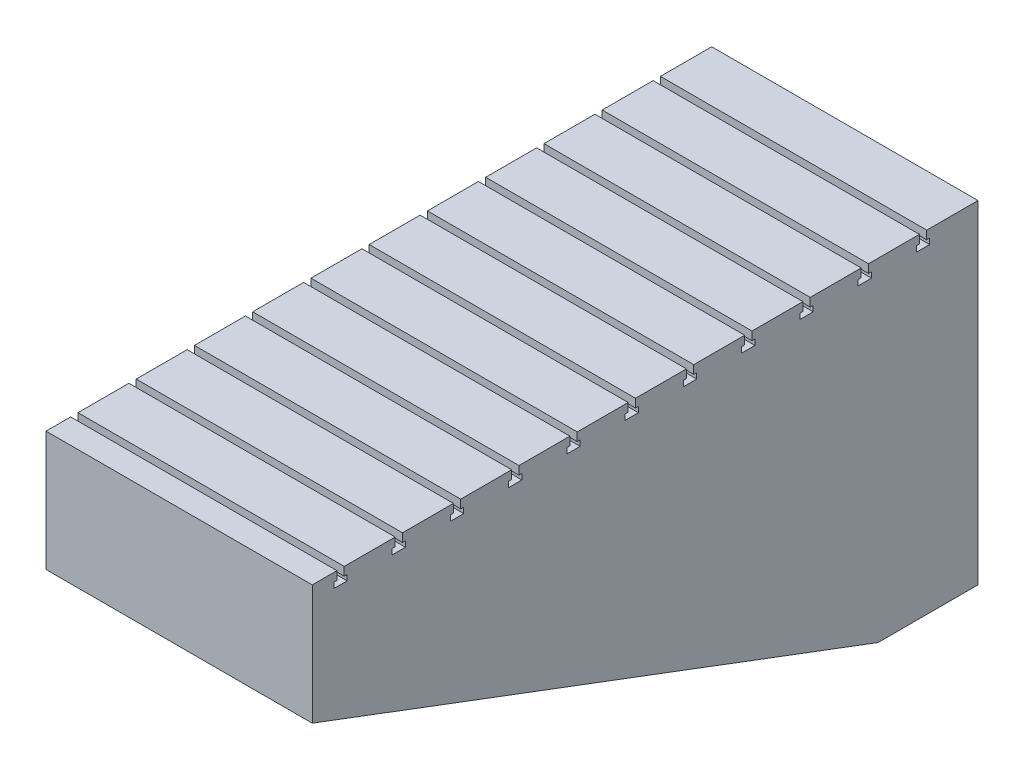
SolidWorks part; units mm, degrees
ref_plane "Front Plane" through (0, 0, 0) normal (0, 0, 1) x (1, 0, 0)
ref_plane "Top Plane" through (0, 0, 0) normal (0, 1, 0) x (1, 0, 0)
ref_plane "Right Plane" through (0, 0, 0) normal (1, 0, 0) x (0, 0, -1)
sketch "Sketch4" plane through (0, 0, 0) normal (1, 0, 0) x (0, 0, -1)
  line L0 (0, 0) -> (-2000, 0)
  line L1 (-2000, 0) -> (-2000, -360)
  line L2 (-2000, -360) -> (-300, -1000)
  line L3 (-300, -1000) -> (0, -1000)
  line L4 (0, -1000) -> (0, 0)
  dimension "D1" = 2000
  dimension "D2" = 1000
  dimension "D3" = 360
  dimension "D4" = 300
extrude "Boss-Extrude1" add sketch "Sketch4" along normal blind 800
sketch "Sketch6" plane through (0, 0, 0) normal (1, 0, 0) x (0, 0, -1)
  line L0 (0, 0) -> (-2000, 0) construction
  line L1 (-154, 0) -> (-176, 0)
  line L2 (-154, 0) -> (-154, -25.3)
  line L3 (-154, -25.3) -> (-145.15, -25.3)
  line L4 (-145.15, -25.3) -> (-145.15, -42)
  line L5 (-145.15, -42) -> (-184.85, -42)
  line L6 (-184.85, -42) -> (-184.85, -25.3)
  line L7 (-184.85, -25.3) -> (-176, -25.3)
  line L8 (-176, -25.3) -> (-176, 0)
  line L9 (-165, 58.1636) -> (-165, 256.6562) construction
  line L11 (0, -1000) -> (0, 0) construction
  dimension "D1" = 22
  dimension "D2" = 39.7
  dimension "D3" = 25.3
  dimension "D4" = 42
  dimension "D5" = 165
  dimension "D6" = 154
extrude "Cut-Extrude1" cut sketch "Sketch6" along normal up to next
pattern_linear "LPattern1" count 11 spacing 175 along (0, 0, 1) of "Cut-Extrude1"
sketch "Sketch7" plane through (0, 0, 0) normal (0, 1, 0) x (1, 0, 0)
  line L0 (800, -165) -> (0, -165) construction
  line L1 (800, -176) -> (0, -176) construction
  line L2 (800, -176) -> (0, -176)
  line L3 (800, -154) -> (0, -154) construction
  line L4 (800, -154) -> (0, -154)
  line L5 (800, -1390) -> (0, -1390) construction
  line L6 (800, -1401) -> (0, -1401) construction
  line L7 (800, -1379) -> (0, -1379) construction
  line L8 (800, -1401) -> (0, -1401)
  line L9 (800, -1379) -> (0, -1379)
